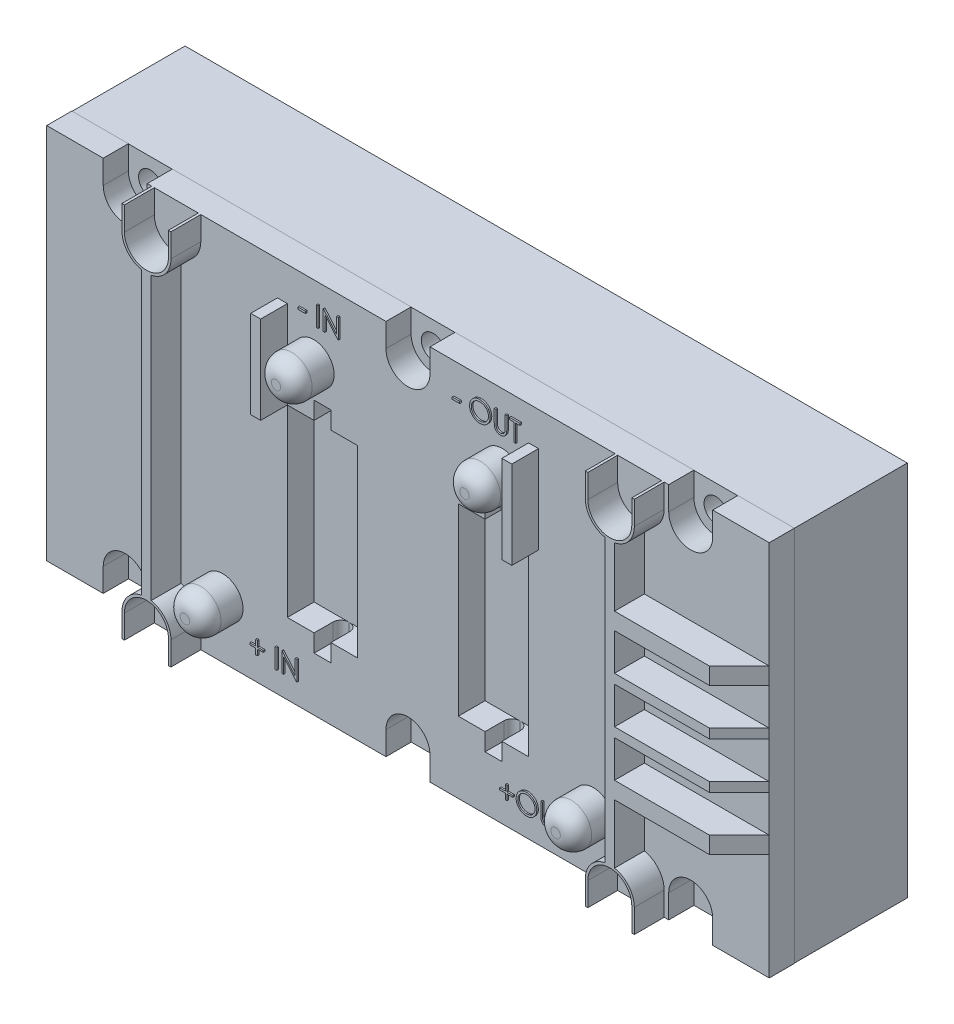
SolidWorks part; units mm, degrees
ref_plane "Front Plane" through (0, 0, 0) normal (0, 0, 1) x (1, 0, 0)
ref_plane "Top Plane" through (0, 0, 0) normal (0, 1, 0) x (1, 0, 0)
ref_plane "Right Plane" through (0, 0, 0) normal (1, 0, 0) x (0, 0, -1)
sketch "Sketch1" plane through (0, 0, 0) normal (0, 0, 1) x (1, 0, 0)
  line L1 (-58.42, -30.48) -> (58.42, -30.48)
  line L2 (-58.42, -30.48) -> (-58.42, 30.48)
  line L3 (-58.42, 30.48) -> (58.42, 30.48)
  line L4 (58.42, -30.48) -> (58.42, 30.48)
  line L5 (-58.42, -30.48) -> (58.42, 30.48) construction
  line L6 (-58.42, 30.48) -> (58.42, -30.48) construction
  point P0 (0, 0)
  dimension "D1" = 60.96
  dimension "D2" = 116.84
extrude "Boss-Extrude1" add sketch "Sketch1" along normal blind 27.178
sketch "Sketch2" plane through (0, 0, 27.178) normal (0, 0, 1) x (1, 0, 0)
  line L0 (58.42, 30.48) -> (-58.42, 30.48) construction
  line L4 (-58.42, 30.48) -> (-58.42, -30.48) construction
  arc A0 (-47.625, 26.67) -> (-43.815, 26.67) centre (-45.72, 26.67) ccw
  arc A1 (-47.625, 26.67) -> (-43.815, 26.67) centre (-45.72, 26.67) cw
  dimension "D1" = 3.81
  dimension "D2" = 3.81
  dimension "D3" = 12.7
extrude "Cut-Extrude1" cut sketch "Sketch2" against normal through all
pattern_linear "LPattern1" count 3 spacing 45.72 along (1, 0, 0) of "Cut-Extrude1"
mirror "Mirror1" about plane through (0, 0, 0) normal (0, 1, 0) of "LPattern1", "Cut-Extrude1"
sketch "Sketch3" plane through (0, 0, 27.178) normal (0, 0, 1) x (1, 0, 0)
  line L0 (-49.276, -26.67) -> (-49.276, -30.48)
  line L1 (-58.42, -30.48) -> (58.42, -30.48) construction
  line L2 (-49.276, -30.48) -> (-42.164, -30.48)
  line L3 (-42.164, -30.48) -> (-42.164, -26.67)
  arc A0 (-42.164, -26.67) -> (-49.276, -26.67) centre (-45.72, -26.67) ccw
  dimension "D1" = 7.112
extrude "Cut-Extrude2" cut sketch "Sketch3" against normal blind 8.89
pattern_linear "LPattern2" count 3 spacing 45.72 along (1, 0, 0) of "Cut-Extrude2"
mirror "Mirror2" about plane through (0, 0, 0) normal (0, 1, 0) of "LPattern2", "Cut-Extrude2"
sketch "Sketch4" plane through (0, 0, 27.178) normal (0, 0, 1) x (1, 0, 0)
  line L0 (-37.465, 26.67) -> (-37.465, -26.67) construction
  line L1 (-41.021, 26.67) -> (-41.021, 30.48)
  line L2 (-3.556, 30.48) -> (-42.164, 30.48) construction
  line L3 (-41.4291, 26.67) -> (-41.4291, 30.48)
  line L4 (-41.4291, 30.48) -> (-41.021, 30.48)
  line L5 (-33.909, 26.67) -> (-33.909, 30.48)
  line L6 (-33.909, 30.48) -> (-33.5009, 30.48)
  line L7 (-33.5009, 30.48) -> (-33.5009, 26.67)
  line L8 (-41.021, -26.67) -> (-41.021, -30.48)
  line L9 (-42.164, -30.48) -> (-3.556, -30.48) construction
  line L10 (-41.021, -30.48) -> (-41.4291, -30.48)
  line L11 (-41.4291, -30.48) -> (-41.4291, -26.67)
  line L12 (-33.909, -26.67) -> (-33.909, -30.48)
  line L13 (-33.909, -30.48) -> (-33.5009, -30.48)
  line L14 (-33.5009, -30.48) -> (-33.5009, -26.67)
  line L15 (-58.42, 30.48) -> (-58.42, -30.48) construction
  line L16 (-45.72, 26.67) -> (-37.465, 26.67) construction
  line L17 (-45.72, -26.67) -> (-37.465, -26.67) construction
  line L18 (-38.227, 22.7798) -> (-38.227, -22.7798)
  line L19 (-36.703, 22.7798) -> (-36.703, -22.7798)
  line L20 (-41.4291, -30.48) -> (-58.42, -30.48)
  line L21 (-36.703, 26.67) -> (-36.703, -26.67) construction
  line L22 (-38.227, 26.67) -> (-38.227, -26.67) construction
  line L23 (-58.42, -30.48) -> (-58.42, 30.48)
  line L24 (-58.42, 30.48) -> (-41.4291, 30.48)
  line L25 (-33.5009, 30.48) -> (0, 30.48)
  line L26 (-3.556, 30.48) -> (3.556, 30.48) construction
  line L27 (0, 30.48) -> (0, -30.48)
  line L28 (-3.556, -30.48) -> (3.556, -30.48) construction
  line L29 (0, -30.48) -> (-33.5009, -30.48)
  line L30 (-41.021, -30.48) -> (-33.909, -30.48)
  line L31 (-41.021, 30.48) -> (-33.909, 30.48)
  arc A0 (-41.021, 26.67) -> (-33.909, 26.67) centre (-37.465, 26.67) ccw
  arc A1 (-33.909, -26.67) -> (-41.021, -26.67) centre (-37.465, -26.67) ccw
  arc A2 (-41.4291, 26.67) -> (-38.227, 22.7798) centre (-37.465, 26.67) ccw
  arc A3 (-33.5009, -26.67) -> (-36.703, -22.7798) centre (-37.465, -26.67) ccw
  arc A4 (-38.227, -22.7798) -> (-41.4291, -26.67) centre (-37.465, -26.67) ccw
  arc A5 (-36.703, 22.7798) -> (-33.5009, 26.67) centre (-37.465, 26.67) ccw
  arc M4 (3.556, 26.67) -> (-3.556, 26.67) centre (0, 26.67) cw
  line M5 (-3.556, 26.67) -> (-3.556, 30.48)
  line M6 (-3.556, 30.48) -> (-42.164, 30.48)
  line M7 (-42.164, 30.48) -> (-42.164, 26.67)
  arc M8 (-42.164, 26.67) -> (-49.276, 26.67) centre (-45.72, 26.67) cw
  line M9 (-49.276, 26.67) -> (-49.276, 30.48)
  line M10 (-49.276, 30.48) -> (-58.42, 30.48)
  line M11 (-58.42, 30.48) -> (-58.42, -30.48)
  line M12 (-58.42, -30.48) -> (-49.276, -30.48)
  line M13 (-49.276, -30.48) -> (-49.276, -26.67)
  arc M14 (-49.276, -26.67) -> (-42.164, -26.67) centre (-45.72, -26.67) cw
  line M15 (-42.164, -26.67) -> (-42.164, -30.48)
  line M16 (-42.164, -30.48) -> (-3.556, -30.48)
  line M17 (-3.556, -30.48) -> (-3.556, -26.67)
  arc M18 (-3.556, -26.67) -> (3.556, -26.67) centre (0, -26.67) cw
  dimension "D1" = 3.556
  dimension "D2" = 0.4081
  dimension "D3" = 20.955
  dimension "D4" = 0.762
  dimension "D5" = 0.762
extrude "Cut-Extrude3" cut sketch "Sketch4" against normal blind 4.826 contours A4 L18 A2 L3 L11 M6 M7 M8 M9 M10 M11 M12 M13 M14 M15 M16 | A5 L19 A3 L14 L27 L7 M16 M17 M18 M4 M5 M6 | L12 A1 L8 M16 | L1 A0 L5 M6
mirror "Mirror3" about plane through (0, 0, 0) normal (1, 0, 0) of "Cut-Extrude3"
sketch "Sketch5" plane through (0, 0, 22.352) normal (0, 0, 1) x (1, 0, 0)
  line L0 (38.227, 22.7798) -> (38.227, -22.7798) construction
  line L1 (58.42, -13.208) -> (38.227, -13.208)
  line L2 (58.42, -13.208) -> (58.42, 13.208)
  line L3 (58.42, 13.208) -> (38.227, 13.208)
  line L4 (38.227, -13.208) -> (38.227, 13.208)
  line L5 (58.42, -13.208) -> (38.227, 13.208) construction
  line L6 (58.42, 13.208) -> (38.227, -13.208) construction
  line L7 (58.42, 30.48) -> (58.42, -30.48) construction
  point P0 (48.3235, 0)
  dimension "D1" = 26.416
extrude "Boss-Extrude2" add sketch "Sketch5" along normal up to surface (4.826 mm away) up to face at (37.465, 0, 27.178)
chamfer "Chamfer1" distance 4.826 angle 45 1 edges at (58.42, 0, 27.178)
sketch "Sketch6" plane through (0, 0, 27.178) normal (0, 0, 1) x (1, 0, 0)
  line L1 (38.227, 10.4775) -> (58.42, 10.4775)
  line L2 (38.227, 10.4775) -> (38.227, 4.5085)
  line L3 (38.227, 4.5085) -> (58.42, 4.5085)
  line L4 (58.42, 10.4775) -> (58.42, 4.5085)
  line L5 (38.227, 22.7798) -> (38.227, 13.208) construction
  line L6 (38.227, 2.9845) -> (58.42, 2.9845)
  line L7 (38.227, 2.9845) -> (38.227, -2.9845)
  line L8 (38.227, -2.9845) -> (58.42, -2.9845)
  line L9 (58.42, 2.9845) -> (58.42, -2.9845)
  line L10 (38.227, -4.5085) -> (58.42, -4.5085)
  line L11 (38.227, -4.5085) -> (38.227, -10.4775)
  line L12 (38.227, -10.4775) -> (58.42, -10.4775)
  line L13 (58.42, -4.5085) -> (58.42, -10.4775)
  line L14 (38.227, 4.5085) -> (38.227, 2.9845) construction
  line L15 (38.227, -2.9845) -> (38.227, -4.5085) construction
  line L16 (38.227, -10.4775) -> (38.227, -13.208) construction
  line L17 (38.227, 10.4775) -> (38.227, 13.208) construction
  line L18 (58.42, 13.208) -> (58.42, -13.208) construction
  dimension "D1" = 5.969
  dimension "D2" = 1.524
extrude "Cut-Extrude4" cut sketch "Sketch6" against normal blind 4.826
sketch "Sketch7" plane through (0, 0, 22.352) normal (0, 0, 1) x (1, 0, 0)
  line L0 (-3.556, 30.48) -> (-33.5009, 30.48) construction
  line L1 (-33.5009, -30.48) -> (-3.556, -30.48) construction
  line L3 (-15.24, 18.796) -> (15.24, 18.796) construction
  line L4 (-29.972, -21.336) -> (29.972, -21.336) construction
  circle A0 centre (-15.24, 18.796) radius 3.302
  circle A1 centre (15.24, 18.796) radius 3.302
  circle A2 centre (29.972, -21.336) radius 3.302
  circle A3 centre (-29.972, -21.336) radius 3.302
  point P12 (0, -21.336)
  point P13 (0, 18.796)
  dimension "D7" = 6.604
  dimension "D1" = 11.684
  dimension "D2" = 9.144
  dimension "D4" = 59.944
  dimension "D6" = 30.48
extrude "Boss-Extrude3" add sketch "Sketch7" along normal blind 6.096
fillet "Fillet1" radius 2.54 4 edges at (33.274, -21.336, 28.448) (18.542, 18.796, 28.448) (-26.67, -21.336, 28.448) (-11.938, 18.796, 28.448)
sketch "Sketch8" plane through (0, 0, 22.352) normal (0, 0, 1) x (1, 0, 0)
  line L1 (-19.505, 10.8018) -> (-8.1477, 10.8018)
  line L2 (-19.505, 10.8018) -> (-19.505, -18.9495)
  line L3 (-19.505, -18.9495) -> (-8.1477, -18.9495)
  line L4 (-8.1477, 10.8018) -> (-8.1477, -18.9495)
extrude "Cut-Extrude5" cut sketch "Sketch8" against normal blind 4.318
sketch "Sketch9" plane through (0, 0, 22.352) normal (0, 0, 1) x (1, 0, 0)
  line L1 (-19.505, 10.8018) -> (-21.1098, 10.8018)
  line L2 (-19.505, 10.8018) -> (-19.505, 24.9985)
  line L3 (-19.505, 24.9985) -> (-21.1098, 24.9985)
  line L4 (-21.1098, 10.8018) -> (-21.1098, 24.9985)
extrude "Boss-Extrude4" add sketch "Sketch9" along normal blind 4.318
sketch "Sketch10" plane through (0, 0, 22.352) normal (0, 0, 1) x (1, 0, 0)
  line L0 (-19.505, 10.8018) -> (-8.1477, -18.9495) construction
  line L2 (-12.4684, -21.7888) -> (-15.1843, -21.7888)
  line L3 (-12.4684, -21.7888) -> (-12.4684, 13.6411)
  line L4 (-12.4684, 13.6411) -> (-15.1843, 13.6411)
  line L5 (-15.1843, -21.7888) -> (-15.1843, 13.6411)
  line L6 (-12.4684, -21.7888) -> (-15.1843, 13.6411) construction
  line L7 (-12.4684, 13.6411) -> (-15.1843, -21.7888) construction
  point P4 (-13.8263, -4.0738)
extrude "Cut-Extrude6" cut sketch "Sketch10" against normal up to surface (4.318 mm away) up to face at (-13.8263, -4.0738, 18.034)
fillet "Fillet2" radius 1.27 4 edges at (-12.4684, -20.3691, 18.034) (-15.1843, -20.3691, 18.034) (-15.1843, 12.2215, 18.034) (-12.4684, 12.2215, 18.034)
mirror "Mirror4" about plane through (0, 0, 0) normal (1, 0, 0) of "Cut-Extrude5", "Boss-Extrude4", "Cut-Extrude6", "Fillet2"
sketch "Sketch11" plane through (0, 0, 22.352) normal (0, 0, 1) x (1, 0, 0)
  text T0 "- IN"
extrude "Boss-Extrude5" add sketch "Sketch11" along normal blind 0.254
sketch "Sketch12" plane through (0, 0, 22.352) normal (0, 0, 1) x (1, 0, 0)
  text T0 "- OUT"
extrude "Boss-Extrude6" add sketch "Sketch12" along normal blind 0.254
sketch "Sketch13" plane through (0, 0, 22.352) normal (0, 0, 1) x (1, 0, 0)
  text T0 "+ IN"
extrude "Boss-Extrude7" add sketch "Sketch13" along normal blind 0.254
sketch "Sketch14" plane through (0, 0, 22.352) normal (0, 0, 1) x (1, 0, 0)
  text T0 "+OUT"
extrude "Boss-Extrude8" add sketch "Sketch14" along normal blind 0.254
sketch "Sketch15" plane through (0, 0, 0) normal (0, 0, -1) x (-1, 0, 0)
  line L0 (-58.42, 30.48) -> (58.42, 30.48) construction
  line L1 (-58.3946, -30.4546) -> (58.3946, -30.4546)
  line L2 (-58.3946, -30.4546) -> (-58.3946, 30.4546)
  line L3 (-58.3946, 30.4546) -> (58.3946, 30.4546)
  line L4 (58.3946, -30.4546) -> (58.3946, 30.4546)
  line L5 (-58.3946, -30.4546) -> (58.3946, 30.4546) construction
  line L6 (-58.3946, 30.4546) -> (58.3946, -30.4546) construction
  line L7 (-58.42, -30.48) -> (58.42, -30.48)
  line L8 (-58.42, -30.48) -> (-58.42, 30.48)
  line L9 (-58.42, 30.48) -> (58.42, 30.48)
  line L10 (58.42, -30.48) -> (58.42, 30.48)
  line L11 (-58.42, -30.48) -> (58.42, 30.48) construction
  line L12 (-58.42, 30.48) -> (58.42, -30.48) construction
  line L13 (58.42, 30.48) -> (58.42, -30.48) construction
  point P0 (0, 0)
  point P6 (0, 0)
  dimension "D1" = 0.0254
  dimension "D2" = 0.0254
extrude "Cut-Extrude7" cut sketch "Sketch15" against normal blind 18.288
